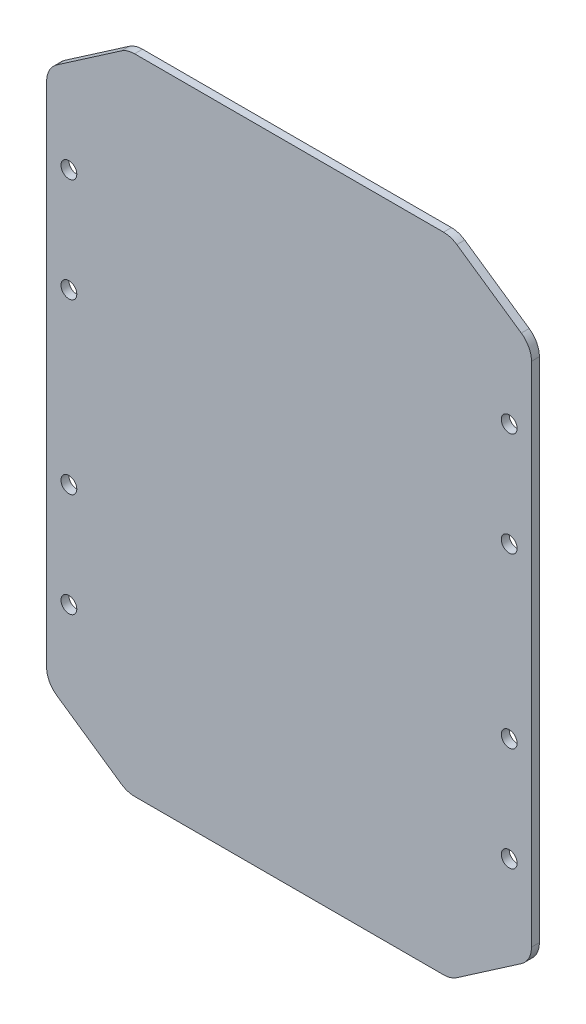
SolidWorks part; units mm, degrees
ref_plane "Спереди" through (0, 0, 0) normal (0, 0, 1) x (1, 0, 0)
ref_plane "Сверху" through (0, 0, 0) normal (0, 1, 0) x (1, 0, 0)
ref_plane "Справа" through (0, 0, 0) normal (1, 0, 0) x (0, 0, -1)
sketch "Эскиз1" plane through (0, 0, 0) normal (0, 0, 1) x (1, 0, 0)
  line L18 (0, 0) -> (0, 50000) construction
  line L19 (0, 0) -> (50000, 0) construction
  line L44 (33.9146, 64.1626) -> (46.9433, 55.194)
  line L45 (-33.9146, 64.1626) -> (-46.9433, 55.194)
  line L46 (-33.9146, 64.1626) -> (-46.9433, 55.194)
  line L47 (-31.2213, 65) -> (31.2213, 65)
  line L48 (-31.2213, -65) -> (31.2213, -65)
  line L49 (-33.9146, -64.1626) -> (-46.9433, -55.194)
  line L50 (33.9146, -64.1626) -> (46.9433, -55.194)
  line L51 (-49, 51.2814) -> (-49, -51.2814)
  line L52 (49, 51.2814) -> (49, -51.2814)
  circle A24 centre (-44.5, 17.0565) radius 1.6 construction
  circle A25 centre (-44.5, 38.0565) radius 1.6 construction
  circle A26 centre (-44.5, 17.0565) radius 1.6
  circle A27 centre (-44.5, 38.0565) radius 1.6
  circle A28 centre (-44.5, -38.0565) radius 1.6
  circle A29 centre (-44.5, -17.0565) radius 1.6
  circle A30 centre (44.5, -17.0565) radius 1.6
  circle A31 centre (44.5, -38.0565) radius 1.6
  circle A32 centre (44.5, 38.0565) radius 1.6
  circle A33 centre (44.5, 17.0565) radius 1.6
  arc A64 (46.9433, 55.194) -> (49, 51.2814) centre (44.25, 51.2814) cw
  arc A65 (31.2213, 65) -> (33.9146, 64.1626) centre (31.2213, 60.25) cw
  arc A66 (-31.2213, 65) -> (-33.9146, 64.1626) centre (-31.2213, 60.25) ccw
  arc A67 (-46.9433, 55.194) -> (-49, 51.2814) centre (-44.25, 51.2814) ccw
  arc A68 (-31.2213, 65) -> (-33.9146, 64.1626) centre (-31.2213, 60.25) ccw
  arc A69 (-46.9433, 55.194) -> (-49, 51.2814) centre (-44.25, 51.2814) ccw
  arc A70 (-46.9433, -55.194) -> (-49, -51.2814) centre (-44.25, -51.2814) cw
  arc A71 (-31.2213, -65) -> (-33.9146, -64.1626) centre (-31.2213, -60.25) cw
  arc A72 (31.2213, -65) -> (33.9146, -64.1626) centre (31.2213, -60.25) ccw
  arc A73 (46.9433, -55.194) -> (49, -51.2814) centre (44.25, -51.2814) ccw
  circle A74 centre (44.5, -38.0565) radius 1.6
  circle A75 centre (-44.5, -38.0565) radius 1.6
  point P45 (0, 0)
  dimension "D1" = 0.25
extrude "Бобышка-Вытянуть1" add sketch "Эскиз1" along normal blind 1.6 contours L50 A73 L52 A64 L44 A65 L47 A68 L46 A69 L51 A70 L49 A71 L48 A72 A33 A29 A26 A27 A28 A30 A31 A32
